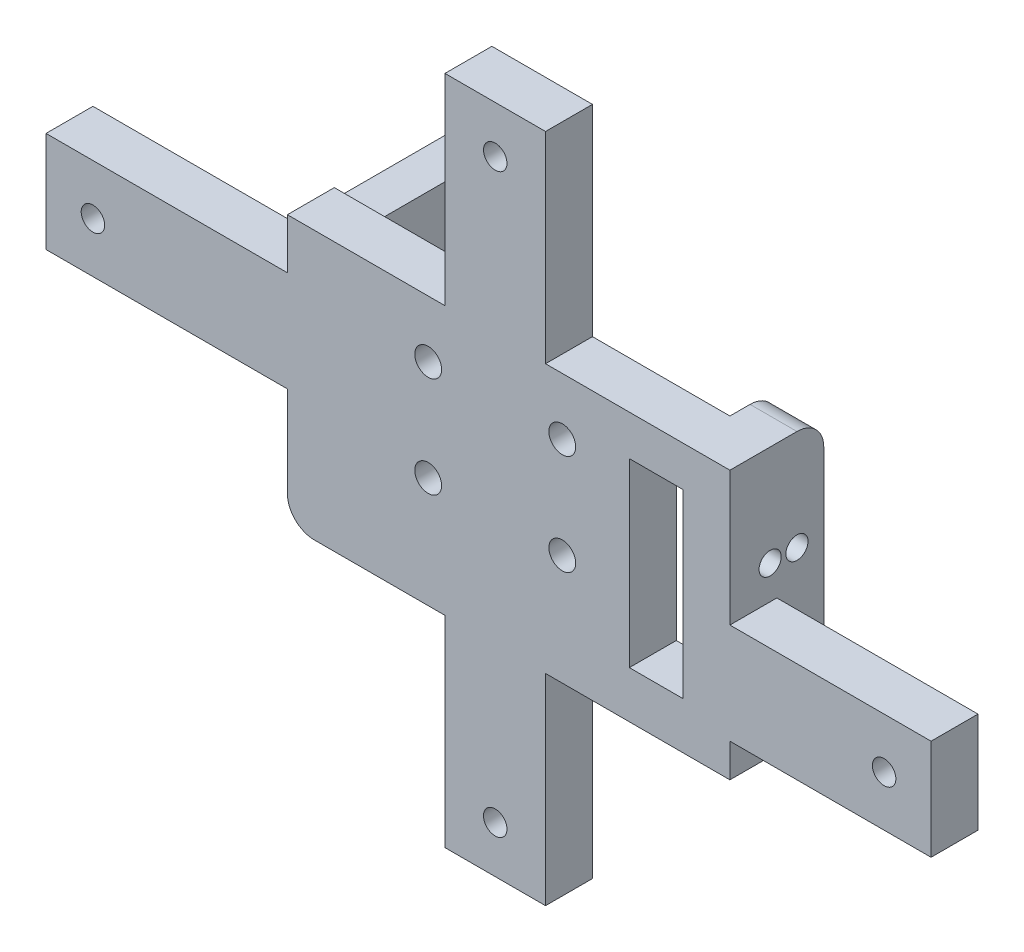
SolidWorks part; units mm, degrees
ref_plane "前视基准面" through (0, 0, 0) normal (0, 0, 1) x (1, 0, 0)
ref_plane "上视基准面" through (0, 0, 0) normal (0, 1, 0) x (1, 0, 0)
ref_plane "右视基准面" through (0, 0, 0) normal (1, 0, 0) x (0, 0, -1)
sketch "草图4" plane through (0, 0, 0) normal (0, 1, 0) x (1, 0, 0)
  line L1 (-21, 22.5) -> (-28, 22.5)
  line L2 (-28, 29.5) -> (28, 29.5)
  line L3 (-28, 29.5) -> (-28, 22.5)
  line L5 (28, 29.5) -> (28, 22.5)
  line L6 (-28, 29.5) -> (-14.4828, 22.5) construction
  line L8 (-21, 22.5) -> (21, 22.5)
  line L16 (21, 22.5) -> (28, 22.5)
  line L18 (14.4828, 22.5) -> (28, 29.5) construction
  dimension "D1" = 29.5
  dimension "D3" = 7
extrude "凸台-拉伸1" add sketch "草图4" against normal blind 6 from surface
sketch "草图5" plane through (0, 0, -29.5) normal (0, 0, -1) x (-1, 0, 0)
  line L0 (0, 4.5795) -> (0, 37.3232) construction
  line L1 (-28, 24.2) -> (28, 24.2) construction
  line L2 (-20, 24.2) -> (20, 24.2)
  line L3 (-20, 24.2) -> (-20, -9.8)
  line L4 (-20, -9.8) -> (20, -9.8)
  line L5 (20, 24.2) -> (20, -9.8)
  line L6 (-20, 24.2) -> (20, -9.8) construction
  line L7 (-20, -9.8) -> (20, 24.2) construction
  line L8 (-20, 14.2) -> (20, 14.2) construction
  circle A0 centre (-10, 21.7) radius 2
  circle A1 centre (10, 21.7) radius 2
  circle A4 centre (10, 6.7) radius 2
  circle A5 centre (-10, 6.7) radius 2
  point P3 (0, 7.2)
  dimension "D3" = 4
  dimension "D1" = 40
  dimension "D2" = 34
  dimension "D4" = 20
  dimension "D6" = 10
  dimension "D7" = 15
extrude "凸台-拉伸2" add sketch "草图5" against normal blind 7
sketch "草图7" plane through (0, 0, 0) normal (0, 1, 0) x (1, 0, 0)
  line L0 (-20, 22.5) -> (-20, 29.5) construction
  line L1 (20, 22.5) -> (-20, 22.5)
  line L2 (20, 22.5) -> (20, 2.5)
  line L3 (17, -0.5) -> (-17, -0.5)
  line L4 (-20, 22.5) -> (-20, 2.5)
  circle A0 centre (10, 10) radius 4.1
  arc A1 (-17, -0.5) -> (-20, 2.5) centre (-17, 2.5) cw
  arc A2 (17, -0.5) -> (20, 2.5) centre (17, 2.5) ccw
  point P14 (20, -0.5)
  dimension "D1" = 8.2
  dimension "D3" = 3
  dimension "D2" = 23
extrude "凸台-拉伸3" add sketch "草图7" along normal blind 7 from surface at -9.8 starting at face at (0, -9.8, -26)
sketch "草图9" plane through (22, 25.2, -43.8683) normal (1, 0, 0) x (0, 0, 1)
  line L0 (26.2748, 10) -> (-30.3655, 10) construction
  line L2 (-8.6317, 2.5) -> (21.3683, 2.5)
  line L4 (-8.6317, 17.5) -> (21.3683, 17.5)
  line L5 (21.3683, 2.5) -> (21.3683, 17.5)
  line L6 (21.3683, 1) -> (21.3683, 28) construction
  circle A0 centre (-8.6317, 10) radius 1.65
  arc A1 (-8.6317, 17.5) -> (-8.6317, 2.5) centre (-8.6317, 10) ccw
  point P2 (-38.5375, 21.5584)
  point P5 (3.8683, 10)
  dimension "D1" = 3.3
  dimension "D3" = 7.5
  dimension "D2" = 15
  dimension "D4" = 30
extrude "凸台-拉伸4" add sketch "草图9" against normal blind 6 from offset 53 separate body offset against normal yes
sketch "草图10" plane through (0, 0, 0) normal (0, 0, 1) x (1, 0, 0)
  line L10 (-31, 30.2) -> (-20, 30.2)
  line L11 (-20, 30.2) -> (-20, -9.8)
  line L13 (-20, -9.8) -> (-27, -9.8)
  line L14 (-31, 30.2) -> (-31, -5.8)
  line L15 (-31, 22.7) -> (-31, 7.7) construction
  arc A1 (-27, -9.8) -> (-31, -5.8) centre (-27, -5.8) cw
  dimension "D1" = 4
extrude "凸台-拉伸5" add sketch "草图10" against normal blind 7 from surface at -22.5 starting at face at (-34, 15.2, -22.5)
sketch "草图14" plane through (0, 0, 0) normal (1, 0, 0) x (0, 0, -1)
  line L0 (22.5, 30.2) -> (29.5, 30.2) construction
  line L6 (22.5, 30.2) -> (32.5, 30.2)
  line L7 (22.5, 30.2) -> (22.5, -9.8)
  line L8 (22.5, -9.8) -> (32.5, -9.8)
  line L9 (36.5, 26.2) -> (36.5, -5.8)
  line L10 (2.5, -9.8) -> (29.5, -9.8) construction
  line L12 (32.5, 15.2) -> (22.5, 15.2) construction
  line L14 (22.5, 24.2) -> (22.5, -2.8) construction
  circle A0 centre (28.5, 15.2) radius 1.65
  circle A1 centre (32.5, 15.2) radius 1.65
  arc A2 (36.5, 26.2) -> (32.5, 30.2) centre (32.5, 26.2) ccw
  arc A3 (32.5, -9.8) -> (36.5, -5.8) centre (32.5, -5.8) ccw
  dimension "D3" = 3.3
  dimension "D4" = 3.3
  dimension "D5" = 4
  dimension "D6" = 4
  dimension "D1" = 6
  dimension "D2" = 4
  dimension "D7" = 4
  dimension "D8" = 15
extrude "凸台-拉伸8" add sketch "草图14" along normal blind 7 from surface at 28 starting at face at (28, 27.2, -26)
sketch "草图15" plane through (0, 0, 0) normal (0, 1, 0) x (1, 0, 0)
  line L0 (20, 29.5) -> (20, 22.5)
  line L3 (28, 29.5) -> (20, 29.5)
  line L5 (20, 22.5) -> (28, 22.5)
  line L6 (28, 22.5) -> (28, 29.5)
extrude "凸台-拉伸9" add sketch "草图15" along normal blind 7 from surface at -9.8 starting at face at (-6.75, -9.8, -13.3447)
sketch "草图17" plane through (-31, 0, 0) normal (1, 0, 0) x (0, 0, -1)
  circle A0 centre (52.5, 15.2) radius 3
  circle A1 centre (52.5, 15.2) radius 1.5
  dimension "D1" = 6
extrude "凸台-拉伸11" add sketch "草图17" along normal blind 0.5
sketch "草图18" plane through (0, 0, -22.5) normal (0, 0, 1) x (1, 0, 0)
  line L1 (25.1335, -11.4356) -> (-25.1335, -11.4356)
  line L2 (25.1335, -11.4356) -> (25.1335, 11.4356)
  line L3 (25.1335, 11.4356) -> (-25.1335, 11.4356)
  line L4 (-25.1335, -11.4356) -> (-25.1335, 11.4356)
  line L5 (25.1335, -11.4356) -> (-25.1335, 11.4356) construction
  line L6 (25.1335, 11.4356) -> (-25.1335, -11.4356) construction
  point P0 (0, 0)
extrude "切除-拉伸1" cut sketch "草图18" along normal blind 50
sketch "草图19" plane through (0, 0, 0) normal (0, 0, 1) x (1, 0, 0)
  line L0 (-31, 30.2) -> (35, 30.2) construction
  line L1 (7.5, 30.2) -> (-7.5, 30.2)
  line L2 (7.5, 30.2) -> (7.5, 60.2)
  line L3 (7.5, 60.2) -> (-7.5, 60.2)
  line L4 (-7.5, 30.2) -> (-7.5, 60.2)
  line L5 (35, -9.8) -> (35, 30.2) construction
  line L6 (-37, 22.7) -> (-67, 22.7)
  line L7 (-37, 22.7) -> (-37, 7.7)
  line L8 (-37, 7.7) -> (-67, 7.7)
  line L9 (-67, 22.7) -> (-67, 7.7)
  line L10 (35, 10.2) -> (65, 10.2)
  line L11 (35, 10.2) -> (35, -4.8)
  line L12 (35, -4.8) -> (65, -4.8)
  line L13 (65, 10.2) -> (65, -4.8)
  line L14 (-27, -9.8) -> (35, -9.8) construction
  line L15 (-7.5, -9.8) -> (7.5, -9.8)
  line L16 (-7.5, -9.8) -> (-7.5, -39.8)
  line L17 (-7.5, -39.8) -> (7.5, -39.8)
  line L18 (7.5, -9.8) -> (7.5, -39.8)
  line L19 (-37, 7.7) -> (-31, 7.7) construction
  line L20 (-67, 15.2) -> (-37, 15.2) construction
  line L21 (0, 80.5223) -> (0, -64.0793) construction
  line L22 (35, 2.7) -> (65, 2.7) construction
  line L23 (-37, 22.7) -> (-31, 22.7) construction
  circle A0 centre (-60, 15.2) radius 1.75
  circle A1 centre (0, 53.2) radius 1.75
  circle A2 centre (0, -32.8) radius 1.75
  circle A3 centre (58, 2.7) radius 1.75
  point P10 (0, 0)
  point P29 (0, 0)
  dimension "D9" = 3.5
  dimension "D1" = 30
  dimension "D2" = 30
  dimension "D3" = 30
  dimension "D4" = 15
  dimension "D5" = 30
  dimension "D6" = 15
  dimension "D7" = 20
  dimension "D8" = 15
  dimension "D10" = 7
  dimension "D11" = 7
  dimension "D12" = 7
  dimension "D13" = 7
extrude "凸台-拉伸12" add sketch "草图19" against normal blind 7 from surface at -22.5 starting at face at (-17.3143, 10.5524, -22.5)
